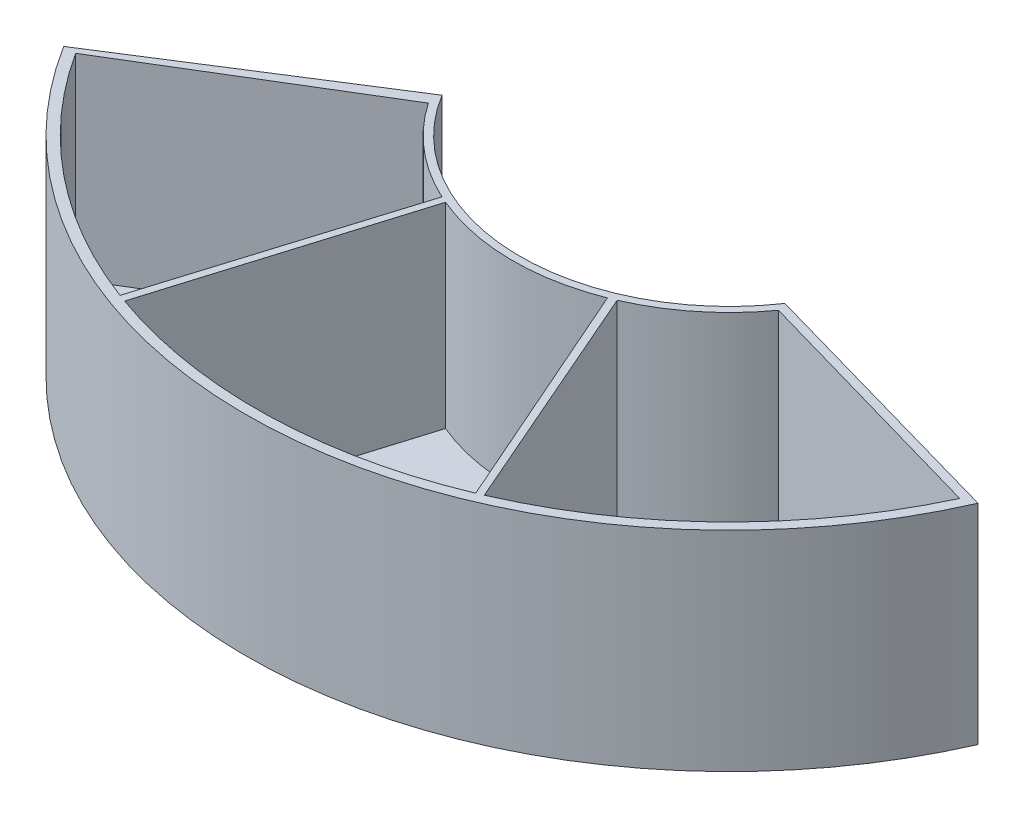
SolidWorks part; units mm, degrees
ref_plane "Front Plane" through (0, 0, 0) normal (0, 0, 1) x (1, 0, 0)
ref_plane "Top Plane" through (0, 0, 0) normal (0, 1, 0) x (1, 0, 0)
ref_plane "Right Plane" through (0, 0, 0) normal (1, 0, 0) x (0, 0, -1)
sketch "Sketch1" plane through (0, 0, 0) normal (0, 1, 0) x (1, 0, 0)
  line L0 (-68.405, -41.5238) -> (-156.9629, -97.7477)
  line L1 (-34.7255, -75.2354) -> (-63.6878, -169.4834)
  line L2 (30.4436, -77.0676) -> (69.9466, -166.9977)
  line L3 (66.213, -44.9368) -> (169.3736, -74.1925)
  line L4 (-152.4012, -97.7477) -> (-68.405, -46.7652)
  line L5 (67.248, -48.4142) -> (164.2782, -76.1145)
  line L6 (-32.2612, -76.3246) -> (-60.9332, -170.4931)
  line L7 (33.0673, -75.9789) -> (72.2518, -166.0133)
  arc A0 (-68.405, -41.5238) -> (66.213, -44.9368) centre (0, 0) ccw
  arc A1 (-156.9629, -97.7477) -> (169.3736, -74.1925) centre (0, 0) ccw
  arc A2 (-152.4012, -97.7477) -> (-63.6878, -169.4834) centre (0, 0) ccw
  arc A3 (-68.405, -46.7652) -> (-34.7255, -75.2354) centre (0, 0) ccw
  arc A4 (-60.9332, -170.4931) -> (69.9466, -166.9977) centre (0, 0) ccw
  arc A5 (72.2518, -166.0133) -> (164.2782, -76.1145) centre (0, 0) ccw
  arc A6 (33.0673, -75.9789) -> (67.248, -48.4142) centre (0, 0) ccw
  arc A7 (-32.2612, -76.3246) -> (30.4436, -77.0676) centre (0, 0) ccw
extrude "Boss-Extrude1" add sketch "Sketch1" along normal blind 80
sketch "Sketch4" plane through (0, 0, 0) normal (0, -1, 0) x (1, 0, 0)
  line L0 (169.3736, 74.1925) -> (66.213, 44.9368) construction
  line L1 (-156.9629, 97.7477) -> (-68.405, 41.5238)
  line L2 (66.213, 44.9368) -> (169.3736, 74.1925)
  arc A0 (-68.405, 41.5238) -> (66.213, 44.9368) centre (0, 0) cw
  arc A1 (-156.9629, 97.7477) -> (169.3736, 74.1925) centre (0, 0) cw
  arc A2 (169.3736, 74.1925) -> (-156.9629, 97.7477) centre (0, 0) ccw construction
extrude "Boss-Extrude2" add sketch "Sketch4" against normal blind 5
